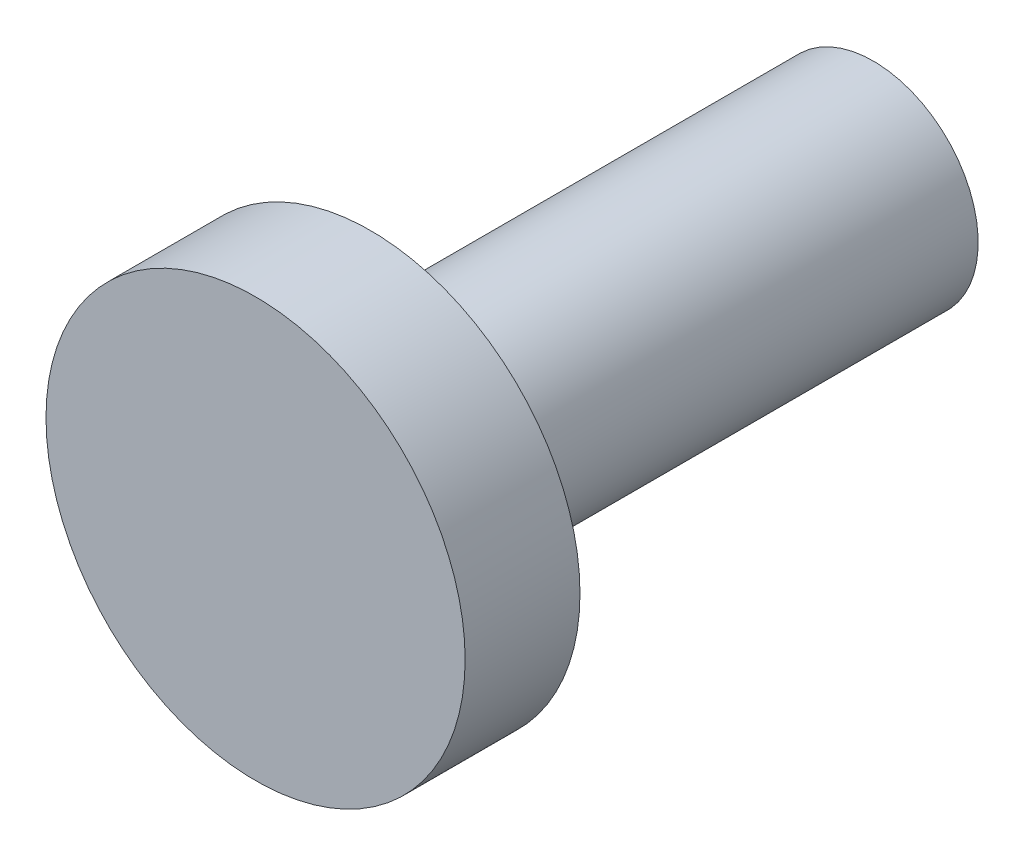
SolidWorks part; units mm, degrees
ref_plane "Plan de face" through (0, 0, 0) normal (0, 0, 1) x (1, 0, 0)
ref_plane "Plan de dessus" through (0, 0, 0) normal (0, 1, 0) x (1, 0, 0)
ref_plane "Plan de droite" through (0, 0, 0) normal (1, 0, 0) x (0, 0, -1)
sketch "Esquisse1" plane through (0, 0, 0) normal (0, 0, 1) x (1, 0, 0)
  circle A0 centre (0, 0) radius 2.5
  dimension "D1" = 5
extrude "Boss.-Extru.1" add sketch "Esquisse1" along normal blind 1.37
sketch "Esquisse2" plane through (0, 0, 0) normal (0, 0, -1) x (-1, 0, 0)
  circle A0 centre (0, 0) radius 1.25
  dimension "D1" = 2.5
extrude "Boss.-Extru.2" add sketch "Esquisse2" along normal blind 6
